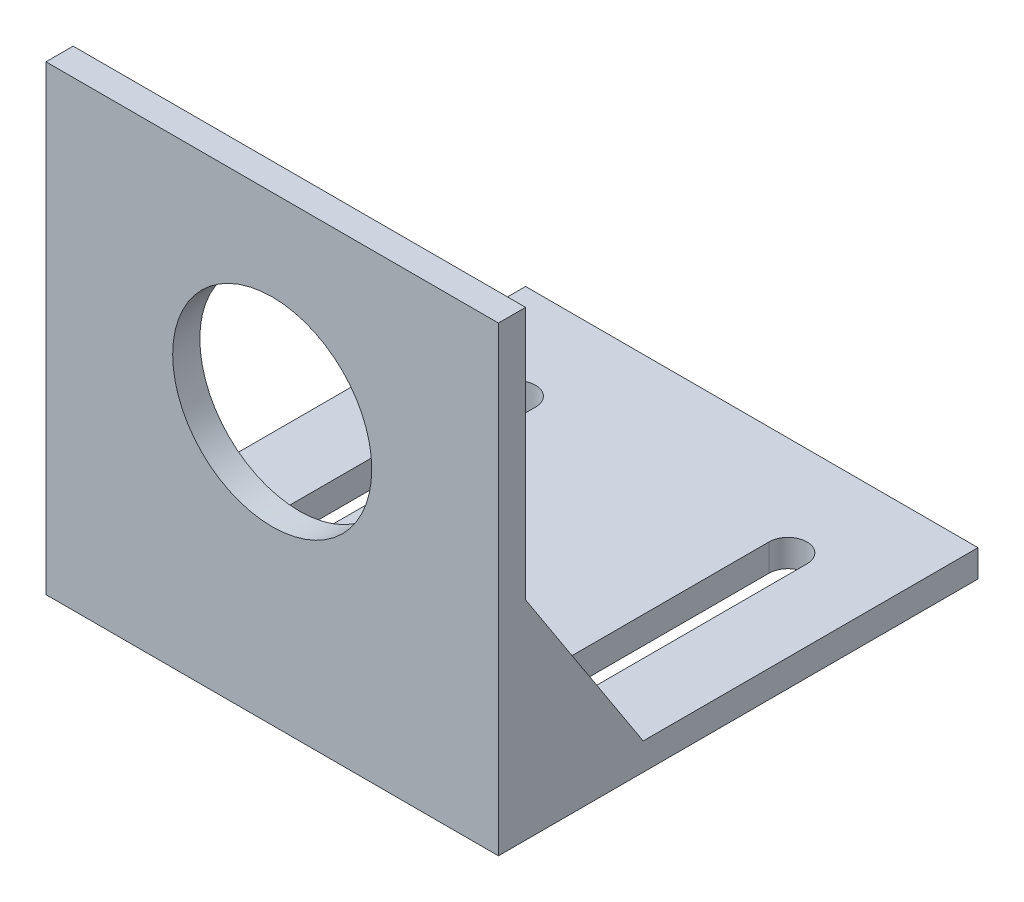
SolidWorks part; units mm, degrees
ref_plane "Front Plane" through (0, 0, 0) normal (0, 0, 1) x (1, 0, 0)
ref_plane "Top Plane" through (0, 0, 0) normal (0, 1, 0) x (1, 0, 0)
ref_plane "Right Plane" through (0, 0, 0) normal (1, 0, 0) x (0, 0, -1)
sketch "Sketch2" plane through (0, 0, 0) normal (0, 1, 0) x (1, 0, 0)
  line L0 (25, 53) -> (25, 0) construction
  line L1 (0, 0) -> (50, 0)
  line L2 (0, 0) -> (0, 53)
  line L3 (0, 53) -> (50, 53)
  line L4 (50, 0) -> (50, 53)
  line L5 (10, 12) -> (10, 42) construction
  line L6 (7.9, 12) -> (7.9, 42)
  line L7 (12.1, 12) -> (12.1, 42)
  line L8 (40, 12) -> (40, 42) construction
  line L9 (42.1, 12) -> (42.1, 42)
  line L10 (37.9, 12) -> (37.9, 42)
  arc A0 (7.9, 12) -> (12.1, 12) centre (10, 12) ccw
  arc A1 (12.1, 42) -> (7.9, 42) centre (10, 42) ccw
  arc A2 (42.1, 12) -> (37.9, 12) centre (40, 12) cw
  arc A3 (37.9, 42) -> (42.1, 42) centre (40, 42) cw
  point P9 (10, 27)
  point P16 (40, 27)
  dimension "D1" = 50
  dimension "D2" = 53
  dimension "D3" = 4.2
  dimension "D4" = 30
  dimension "D5" = 11
  dimension "D6" = 15
extrude "Boss-Extrude1" add sketch "Sketch2" along normal blind 3
sketch "Sketch3" plane through (0, 0, 0) normal (0, 0, 1) x (1, 0, 0)
  line L0 (0, 0) -> (50, 0) construction
  line L1 (50, 3) -> (50, 0) construction
  line L2 (0, 3) -> (50, 3)
  line L3 (0, 3) -> (0, 51)
  line L4 (0, 51) -> (50, 51)
  line L5 (50, 3) -> (50, 51)
  circle A1 centre (25, 30) radius 11
  point P12 (25, 51)
  dimension "D2" = 22
  dimension "D3" = 30
  dimension "D4" = 48
extrude "Boss-Extrude2" add sketch "Sketch3" against normal blind 3
sketch "Sketch4" plane through (50, 0, 0) normal (1, 0, 0) x (0, 0, -1)
  line L0 (16, 3) -> (3, 23)
  line L1 (3, 3) -> (53, 3) construction
  line L2 (3, 3) -> (3, 51) construction
  line L3 (3, 23) -> (3, 3)
  line L4 (3, 3) -> (16, 3)
  dimension "D1" = 13
  dimension "D2" = 20
extrude "Boss-Extrude3" add sketch "Sketch4" against normal blind 3
ref_plane "Plane1" through (25, 0, 0) normal (-1, 0, 0) x (0, 0, 1)
mirror "Mirror1" about plane through (25, 0, 0) normal (-1, 0, 0) of "Boss-Extrude3"
